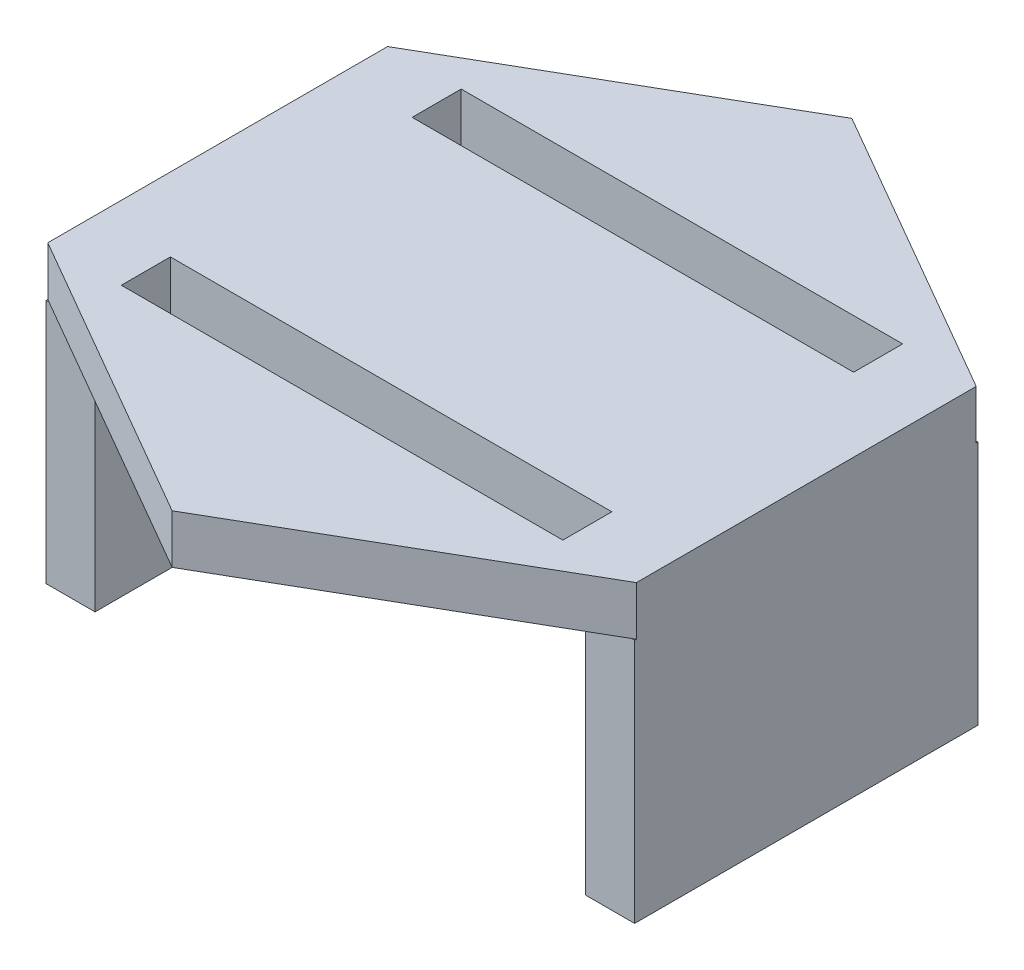
SolidWorks part; units mm, degrees
ref_plane "Front Plane" through (0, 0, 0) normal (0, 0, 1) x (1, 0, 0)
ref_plane "Top Plane" through (0, 0, 0) normal (0, 1, 0) x (1, 0, 0)
ref_plane "Right Plane" through (0, 0, 0) normal (1, 0, 0) x (0, 0, -1)
sketch "Sketch1" plane through (0, 0, 0) normal (0, 1, 0) x (1, 0, 0)
  line L1 (0, 0) -> (12.7, 0)
  line L2 (0, 0) -> (0, 88.9)
  line L3 (0, 88.9) -> (12.7, 88.9)
  line L4 (12.7, 0) -> (12.7, 88.9)
  line L5 (-127, 0) -> (-139.7, 0)
  line L6 (-127, 0) -> (-127, 88.9)
  line L7 (-127, 88.9) -> (-139.7, 88.9)
  line L8 (-139.7, 0) -> (-139.7, 88.9)
  dimension "D1" = 88.9
  dimension "D2" = 12.7
  dimension "D3" = 152.4
extrude "Boss-Extrude1" add sketch "Sketch1" along normal blind 63.5
sketch "Sketch2" plane through (0, 63.5, 0) normal (0, 1, 0) x (1, 0, 0)
  line L0 (12.7, 0) -> (12.7, 88.9) construction
  line L1 (-63.5, -43.5382) -> (12.7, 0.4559)
  line L2 (12.7, 0.4559) -> (12.7, 88.4441)
  line L3 (12.7, 88.4441) -> (-63.5, 132.4382)
  line L4 (-63.5, 132.4382) -> (-139.7, 88.4441)
  line L5 (-139.7, 88.4441) -> (-139.7, 0.4559)
  line L6 (-139.7, 0.4559) -> (-63.5, -43.5382)
  line L8 (-139.7, 88.9) -> (-139.7, 0) construction
  circle A0 centre (-63.5, 44.45) radius 76.2 construction
  point P12 (-139.7, 44.45)
  point P13 (-139.7, 44.45)
extrude "Boss-Extrude2" add sketch "Sketch2" along normal blind 12.7
sketch "Sketch3" plane through (0, 76.2, 0) normal (0, 1, 0) x (1, 0, 0)
  line L1 (-120.65, 0.4559) -> (-6.35, 0.4559)
  line L2 (-120.65, 0.4559) -> (-120.65, 13.1559)
  line L3 (-120.65, 13.1559) -> (-6.35, 13.1559)
  line L4 (-6.35, 0.4559) -> (-6.35, 13.1559)
  line L5 (-6.35, 88.4441) -> (-120.65, 88.4441)
  line L6 (-6.35, 88.4441) -> (-6.35, 75.7441)
  line L7 (-6.35, 75.7441) -> (-120.65, 75.7441)
  line L8 (-120.65, 88.4441) -> (-120.65, 75.7441)
  point P8 (-63.5, 88.4441)
  point P13 (-63.5, 13.1559)
  dimension "D1" = 114.3
  dimension "D2" = 12.7
extrude "Cut-Extrude1" cut sketch "Sketch3" against normal through all
